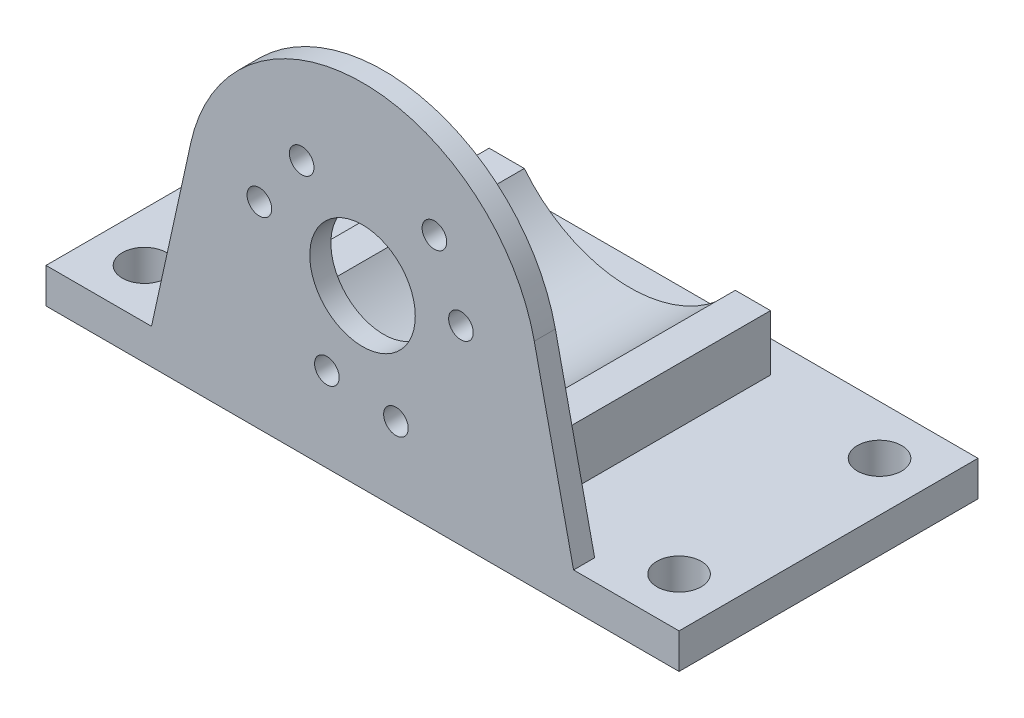
SolidWorks part; units mm, degrees
material "Plain Carbon Steel"
ref_plane "Front Plane" through (0, 0, 0) normal (0, 0, 1) x (1, 0, 0)
ref_plane "Top Plane" through (0, 0, 0) normal (0, 1, 0) x (1, 0, 0)
ref_plane "Right Plane" through (0, 0, 0) normal (1, 0, 0) x (0, 0, -1)
sketch "Sketch3" plane through (0, 0, 0) normal (0, 1, 0) x (1, 0, 0)
  line L0 (-40.6832, 0) -> (52.6999, 0) construction
  line L1 (-45, 21.25) -> (45, 21.25)
  line L2 (-45, 21.25) -> (-45, -21.25)
  line L3 (-45, -21.25) -> (45, -21.25)
  line L4 (45, 21.25) -> (45, -21.25)
  line L5 (0, 26.2262) -> (0, -26.6116) construction
  circle A0 centre (-38, 14.25) radius 3.15
  circle A4 centre (38, 14.25) radius 3.15
  circle A5 centre (38, -14.25) radius 3.15
  circle A6 centre (-38, -14.25) radius 3.15
  point P0 (0, -21.25)
  point P5 (45, 0)
  dimension "D5" = 6.3
  dimension "D1" = 42.5
  dimension "D2" = 90
  dimension "D3" = 7
  dimension "D4" = 7
extrude "Boss-Extrude1" add sketch "Sketch3" along normal blind 5
sketch "Sketch4" plane through (0, 0, 21.25) normal (0, 0, 1) x (1, 0, 0)
  line L2 (30, 5) -> (24.4157, 30.3735)
  line L3 (-30, 5) -> (-24.4157, 30.3735)
  line L4 (-45, 5) -> (45, 5) construction
  line L6 (-30, 5) -> (30, 5)
  circle A1 centre (0, 25) radius 19
  circle A2 centre (0, 25) radius 3
  circle A3 centre (13.9904, 27.0801) radius 1.75
  circle A4 centre (10.2192, 36.3473) radius 1.75
  circle A5 centre (-8.6549, 36.0875) radius 1.75
  circle A6 centre (-14.6673, 27.9923) radius 1.75
  circle A7 centre (-5.0673, 12.0109) radius 1.75
  circle A8 centre (4.7494, 10.6747) radius 1.75
  circle A9 centre (0, 25) radius 7.5
  arc A10 (24.4157, 30.3735) -> (-24.4157, 30.3735) centre (0, 25) ccw
  point P8 (0, 25)
  line M7 (45, 5) -> (-45, 5)
  dimension "D1" = 38
  dimension "D2" = 6
  dimension "D3" = 3.5
  dimension "D4" = 13.9904
  dimension "D5" = 2.0801
  dimension "D6" = 4.7494
  dimension "D8" = 12.9891
  dimension "D17" = 15
  dimension "D18" = 50
  dimension "D7" = 14.3253
  dimension "D10" = 2.9923
  dimension "D9" = 5.0673
  dimension "D11" = 14.6673
  dimension "D12" = 8.6549
  dimension "D13" = 11.0875
  dimension "D14" = 11.3473
  dimension "D15" = 10.2192
  dimension "D16" = 25
  dimension "D19" = 15
  dimension "D20" = 15
extrude "Boss-Extrude2" add sketch "Sketch4" against normal blind 3 contours A1 A8 A7 A6 A5 A4 A3 A2 | A1 L3 L2 M7
sketch "Sketch5" plane through (0, 0, 18.25) normal (0, 0, -1) x (-1, 0, 0)
  line L1 (-15, 12.9351) -> (-15, 0)
  line L5 (-45, 0) -> (45, 0) construction
  line L7 (-15, 0) -> (15, 0)
  line L9 (15, 0) -> (15, 12.9351)
  line L11 (-20, 12.9351) -> (20, 12.9351)
  line L12 (-20, 12.9351) -> (-20, 0)
  line L13 (-20, 0) -> (20, 0)
  line L14 (20, 12.9351) -> (20, 0)
  circle A3 centre (0, 25) radius 7.5 construction
  circle A4 centre (0, 25) radius 7.5
  circle A5 centre (0, 25) radius 19.25
  line M36 (-30, 5) -> (30, 5)
  dimension "D2" = 30
  dimension "D1" = 38.5
  dimension "D3" = 5
extrude "Boss-Extrude3" add sketch "Sketch5" along normal blind 35 contours A5 L1 L9 M36 | L11 L12 L1 M36 | L14 L11 L9 M36
